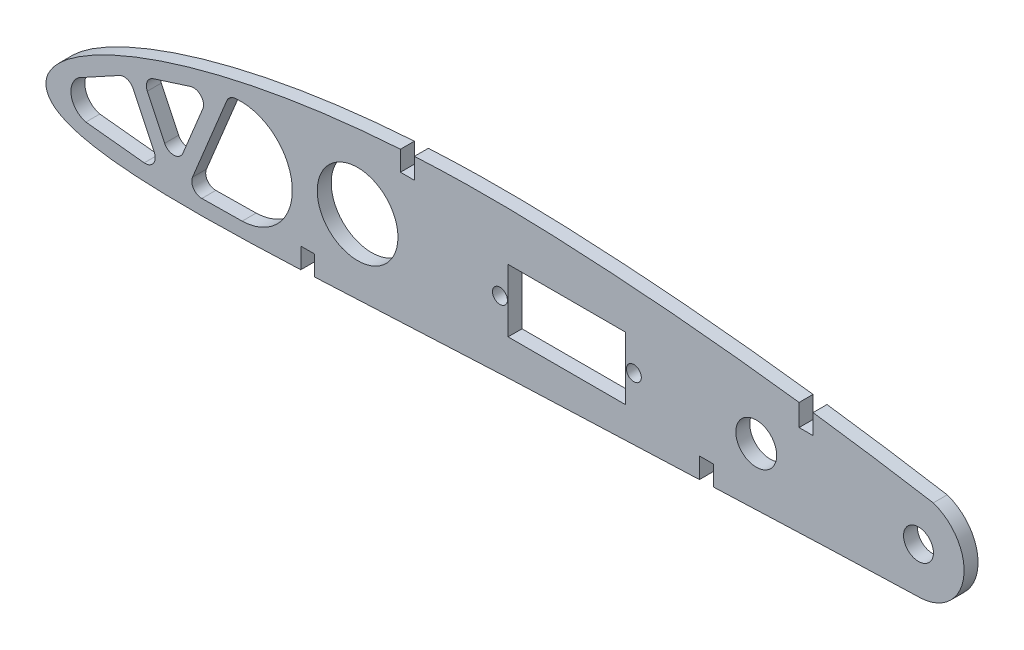
SolidWorks part; units mm, degrees
material "Фанера"
ref_plane "Front" through (0, 0, 0) normal (0, 0, 1) x (1, 0, 0)
ref_plane "Top" through (0, 0, 0) normal (0, 1, 0) x (1, 0, 0)
ref_plane "Right" through (0, 0, 0) normal (1, 0, 0) x (0, 0, -1)
curve "Кривая1"
  spline degree 3 poles (0.048, 0.6214, 0) (0.0227, 0.3735, 0) (-0.0278, -0.1225, 0) (0.078, -0.8844, 0) (0.3497, -1.6388, 0) (0.8143, -2.3651, 0) (1.4635, -3.0393, 0) (2.291, -3.661, 0) (3.3059, -4.2358, 0) (4.5353, -4.7737, 0) (6.0297, -5.2822, 0) (7.869, -5.7653, 0) (10.1688, -6.2217, 0) (13.0754, -6.6396, 0) (16.7281, -6.993, 0) (21.19, -7.2473, 0) (26.4, -7.3766, 0) (32.1974, -7.3763, 0) (38.3978, -7.2614, 0) (44.8576, -7.0566, 0) (51.4865, -6.7865, 0) (58.231, -6.4723, 0) (65.0521, -6.1329, 0) (71.9108, -5.784, 0) (78.7714, -5.4397, 0) (85.6105, -5.111, 0) (92.4321, -4.805, 0) (99.255, -4.532, 0) (106.0974, -4.2783, 0) (112.9692, -4.0031, 0) (119.8644, -3.7232, 0) (126.7739, -3.4401, 0) (133.6816, -3.1587, 0) (140.5819, -2.8824, 0) (147.472, -2.6139, 0) (154.3526, -2.3556, 0) (161.225, -2.1094, 0) (168.0909, -1.8766, 0) (174.9516, -1.6586, 0) (181.8086, -1.4564, 0) (188.6632, -1.2704, 0) (195.5166, -1.1011, 0) (202.3695, -0.9486, 0) (209.2212, -0.8129, 0) (216.0668, -0.6936, 0) (222.8864, -0.5903, 0) (229.6176, -0.5029, 0) (236.0874, -0.4315, 0) (241.9808, -0.3765, 0) (246.559, -0.3395, 0) (249.1205, -0.3213, 0) (250, -0.315, 0) knots 0 0 0 0 0.002941 0.005884 0.009016 0.012365 0.016008 0.020037 0.024574 0.029784 0.035897 0.04324 0.052276 0.063635 0.077983 0.095698 0.11652 0.139661 0.164312 0.189919 0.216157 0.242838 0.269834 0.296993 0.324123 0.351139 0.378036 0.404946 0.431961 0.459078 0.486347 0.513641 0.540929 0.568176 0.59538 0.622543 0.649673 0.676775 0.703855 0.730919 0.757971 0.785018 0.812062 0.839103 0.866132 0.893099 0.919831 0.94581 0.969681 0.98959 1 1 1 1
curve "Кривая2"
  spline degree 3 poles (250, 0.315, 0) (249.1557, 0.545, 0) (246.7202, 1.2085, 0) (242.3913, 2.3583, 0) (236.8498, 3.7876, 0) (230.7799, 5.298, 0) (224.4559, 6.8129, 0) (218.0305, 8.2916, 0) (211.5624, 9.7197, 0) (205.0724, 11.0924, 0) (198.568, 12.4079, 0) (192.0524, 13.6653, 0) (185.5276, 14.8641, 0) (178.9953, 16.0034, 0) (172.4571, 17.0824, 0) (165.9143, 18.0998, 0) (159.3687, 19.0545, 0) (152.8218, 19.9449, 0) (146.2754, 20.7693, 0) (139.7314, 21.5257, 0) (133.1918, 22.212, 0) (126.6587, 22.8257, 0) (120.1368, 23.364, 0) (113.6286, 23.8247, 0) (107.1527, 24.2002, 0) (100.7411, 24.4984, 0) (94.4118, 24.6866, 0) (88.1559, 24.7401, 0) (81.949, 24.6588, 0) (75.7805, 24.441, 0) (69.6537, 24.0819, 0) (63.5754, 23.578, 0) (57.5552, 22.9249, 0) (51.6058, 22.1191, 0) (45.7444, 21.1566, 0) (39.9959, 20.0354, 0) (34.3979, 18.7563, 0) (29.0104, 17.3276, 0) (23.9258, 15.7719, 0) (19.2707, 14.1343, 0) (15.1791, 12.4833, 0) (11.7405, 10.8956, 0) (8.9594, 9.4296, 0) (6.7609, 8.1086, 0) (5.0337, 6.9246, 0) (3.6717, 5.8542, 0) (2.5921, 4.8713, 0) (1.7382, 3.9526, 0) (1.0699, 3.0809, 0) (0.5716, 2.2416, 0) (0.2158, 1.4308, 0) (0.1023, 0.8832, 0) (0.048, 0.6214, 0) knots 0 0 0 0 0.010162 0.029313 0.052012 0.076619 0.101948 0.127526 0.153184 0.178868 0.204558 0.230246 0.255926 0.281594 0.307246 0.332878 0.358485 0.384061 0.409603 0.435104 0.460559 0.485959 0.511303 0.536552 0.561723 0.586629 0.611085 0.635251 0.659272 0.683164 0.706922 0.730536 0.753983 0.777235 0.800246 0.822951 0.845237 0.866916 0.887662 0.906968 0.924203 0.938879 0.950932 0.960693 0.968647 0.975233 0.980795 0.985584 0.989782 0.993521 0.996902 1 1 1 1
sketch "Эскиз2" plane through (0, 0, 0) normal (0, 0, 1) x (1, 0, 0)
  line L0 (-1.2592, 0) -> (250.7702, 0) construction
  line L1 (250.1305, 0) -> (250.1305, 80.0888) construction
  line L2 (0, 0) -> (0, 69.7453) construction
  line L3 (62.5326, 123.1249) -> (62.5326, -48.5934) construction
  line L4 (142.5326, 131.1199) -> (142.5326, -55.0117) construction
  line L5 (62.5326, 8.5923) -> (142.5326, 8.6947) construction
  line L6 (62.5326, 8.5923) -> (150.6431, 8.5923) construction
  line L7 (175.0913, 92.567) -> (175.0913, -39.4544) construction
  line L8 (165.9405, 18.0854) -> (165.9405, -1.9504)
  line L18 (17.4887, 7.868) -> (21.7254, -1.0733)
  line L19 (29.4016, -1.5679) -> (36.2887, 15.1777)
  line L20 (20.3422, 8.8519) -> (23.813, 1.5271)
  line L21 (27.4701, 1.6228) -> (31.461, 11.3265)
  line L22 (7.9994, -2.6904) -> (19.7094, -3.9188)
  line L23 (31.2779, -4.3285) -> (39.3668, -4.221)
  line L24 (6.5801, 4.311) -> (14.7212, 8.7661)
  line L25 (21.5421, 11.6138) -> (29.0038, 13.9928)
  line L26 (72.5326, 27.406) -> (72.5326, 20.4403) construction
  line L27 (52.5326, -12.1202) -> (52.5326, -2.6904) construction
  line L28 (152.5326, 24.4982) -> (152.5326, 15.921) construction
  line L29 (132.5326, -7.5811) -> (132.5326, 3.1811) construction
  line L30 (151.1326, 20.1529) -> (151.1326, 15.7875)
  line L31 (151.1326, 15.7875) -> (153.9326, 15.7875)
  line L32 (153.9326, 15.7875) -> (153.9326, 19.7875)
  line L33 (131.1326, -3.2627) -> (131.1326, 0.8506)
  line L34 (131.1326, 0.8506) -> (133.9326, 0.8506)
  line L35 (133.9326, 0.8506) -> (133.9326, -3.1494)
  line L36 (71.1326, 24.1575) -> (71.1326, 20.1575)
  line L37 (71.1326, 20.1575) -> (73.9326, 20.1575)
  line L38 (73.9326, 20.1575) -> (73.9326, 24.3239)
  line L39 (51.1326, -6.7954) -> (51.1326, -2.6707)
  line L40 (51.1326, -2.6707) -> (53.9326, -2.6707)
  line L41 (53.9326, -2.6707) -> (53.9326, -6.6707)
  line L42 (116.3326, 14.946) -> (119.6026, 14.946) construction
  line L43 (92.7326, 2.346) -> (116.3326, 2.346)
  line L44 (92.7326, 2.346) -> (92.7326, 14.946)
  line L45 (92.7326, 14.946) -> (116.3326, 14.946)
  line L46 (116.3326, 2.346) -> (116.3326, 14.946)
  line L47 (92.7326, 2.346) -> (116.3326, 14.946) construction
  line L48 (92.7326, 14.946) -> (116.3326, 2.346) construction
  line L49 (119.6026, 14.946) -> (119.6026, 2.346) construction
  line L50 (119.6026, 2.346) -> (116.3326, 2.346) construction
  line L51 (104.5326, 11.3265) -> (104.5326, 5.8512) construction
  arc A0 (250, 0.315) -> (250, -0.315) centre (249.685, 0) cw
  circle A3 centre (62.5326, 8.5923) radius 8.1
  circle A5 centre (62.5326, 8.5923) radius 80 construction
  circle A6 centre (142.5326, 8.6947) radius 4.1
  arc A7 (175.0913, 16.6448) -> (175.0913, -1.657) centre (175.0913, 7.4939) ccw
  arc A16 (37.9117, 16.4041) -> (36.2887, 15.1777) centre (38.1384, 14.417) ccw
  arc A20 (6.5801, 4.311) -> (7.9994, -2.6904) centre (8.9558, 1.1481) ccw
  arc A21 (37.9117, 16.4041) -> (39.3668, -4.221) centre (39.0848, 6.123) cw
  arc A22 (23.813, 1.5271) -> (27.4701, 1.6228) centre (25.6204, 2.3835) ccw
  arc A23 (31.461, 11.3265) -> (29.0038, 13.9928) centre (29.6113, 12.0873) ccw
  arc A24 (20.3422, 8.8519) -> (21.5421, 11.6138) centre (22.1496, 9.7083) cw
  arc A25 (17.4887, 7.868) -> (14.7212, 8.7661) centre (15.6813, 7.0116) ccw
  arc A26 (19.7094, -3.9188) -> (21.7254, -1.0733) centre (19.9181, -1.9297) ccw
  arc A27 (29.4016, -1.5679) -> (31.2779, -4.3285) centre (31.2513, -2.3286) ccw
  circle A28 centre (175.0913, 7.4939) radius 3
  circle A29 centre (117.9676, 8.6632) radius 1.5
  circle A30 centre (91.0976, 8.6632) radius 1.5
  circle A31 centre (175.0913, 7.4939) radius 9.1509
  spline S0 degree 3 poles (250, 0.315) (249.1557, 0.545) (246.7202, 1.2085) (242.3913, 2.3583) (236.8498, 3.7876) (230.7799, 5.298) (224.4559, 6.8129) (218.0305, 8.2916) (211.5624, 9.7197) (205.0724, 11.0924) (198.568, 12.4079) (192.0524, 13.6653) (185.5276, 14.8641) (178.9953, 16.0034) (172.4571, 17.0824) (165.9143, 18.0998) (159.3687, 19.0545) (152.8218, 19.9449) (146.2754, 20.7693) (139.7314, 21.5257) (133.1918, 22.212) (126.6587, 22.8257) (120.1368, 23.364) (113.6286, 23.8247) (107.1527, 24.2002) (100.7411, 24.4984) (94.4118, 24.6866) (88.1559, 24.7401) (81.949, 24.6588) (75.7805, 24.441) (69.6537, 24.0819) (63.5754, 23.578) (57.5552, 22.9249) (51.6058, 22.1191) (45.7444, 21.1566) (39.9959, 20.0354) (34.3979, 18.7563) (29.0104, 17.3276) (23.9258, 15.7719) (19.2707, 14.1343) (15.1791, 12.4833) (11.7405, 10.8956) (8.9594, 9.4296) (6.7609, 8.1086) (5.0337, 6.9246) (3.6717, 5.8542) (2.5921, 4.8713) (1.7382, 3.9526) (1.0699, 3.0809) (0.5716, 2.2416) (0.2158, 1.4308) (0.1023, 0.8832) (0.048, 0.6214) knots 0 0 0 0 0.010162 0.029313 0.052012 0.076619 0.101948 0.127526 0.153184 0.178868 0.204558 0.230246 0.255926 0.281594 0.307246 0.332878 0.358485 0.384061 0.409603 0.435104 0.460559 0.485959 0.511303 0.536552 0.561723 0.586629 0.611085 0.635251 0.659272 0.683164 0.706922 0.730536 0.753983 0.777235 0.800246 0.822951 0.845237 0.866916 0.887662 0.906968 0.924203 0.938879 0.950932 0.960693 0.968647 0.975233 0.980795 0.985584 0.989782 0.993521 0.996902 1 1 1 1 construction
  spline S1 degree 3 poles (0.048, 0.6214) (0.0227, 0.3735) (-0.0278, -0.1225) (0.078, -0.8844) (0.3497, -1.6388) (0.8143, -2.3651) (1.4635, -3.0393) (2.291, -3.661) (3.3059, -4.2358) (4.5353, -4.7737) (6.0297, -5.2822) (7.869, -5.7653) (10.1688, -6.2217) (13.0754, -6.6396) (16.7281, -6.993) (21.19, -7.2473) (26.4, -7.3766) (32.1974, -7.3763) (38.3978, -7.2614) (44.8576, -7.0566) (51.4865, -6.7865) (58.231, -6.4723) (65.0521, -6.1329) (71.9108, -5.784) (78.7714, -5.4397) (85.6105, -5.111) (92.4321, -4.805) (99.255, -4.532) (106.0974, -4.2783) (112.9692, -4.0031) (119.8644, -3.7232) (126.7739, -3.4401) (133.6816, -3.1587) (140.5819, -2.8824) (147.472, -2.6139) (154.3526, -2.3556) (161.225, -2.1094) (168.0909, -1.8766) (174.9516, -1.6586) (181.8086, -1.4564) (188.6632, -1.2704) (195.5166, -1.1011) (202.3695, -0.9486) (211.4992, -0.7677) (220.6031, -0.6199) (229.6176, -0.5029) (236.0874, -0.4315) (241.9808, -0.3765) (246.559, -0.3395) (249.1205, -0.3213) (250, -0.315) knots 0 0 0 0 0.002941 0.005884 0.009016 0.012365 0.016008 0.020037 0.024574 0.029784 0.035897 0.04324 0.052276 0.063635 0.077983 0.095698 0.11652 0.139661 0.164312 0.189919 0.216157 0.242838 0.269834 0.296993 0.324123 0.351139 0.378036 0.404946 0.431961 0.459078 0.486347 0.513641 0.540929 0.568176 0.59538 0.622543 0.649673 0.676775 0.703855 0.730919 0.757971 0.785018 0.812062 0.839103 0.893099 0.919831 0.94581 0.969681 0.98959 1 1 1 1 construction
  spline S2 degree 3 poles (250, 0.315) (249.1557, 0.545) (246.7202, 1.2085) (242.3913, 2.3583) (236.8498, 3.7876) (230.7799, 5.298) (224.4559, 6.8129) (218.0305, 8.2916) (211.5624, 9.7197) (205.0724, 11.0924) (198.568, 12.4079) (192.0524, 13.6653) (185.5276, 14.8641) (178.9953, 16.0034) (172.4571, 17.0824) (165.9143, 18.0998) (159.7397, 19.0004) (155.7443, 19.5471) (153.9326, 19.7875) knots 0 0 0 0 0.010162 0.029313 0.052012 0.076619 0.101948 0.127526 0.153184 0.178868 0.204558 0.230246 0.255926 0.281594 0.307246 0.332878 0.358485 0.379707 0.379707 0.379707 0.379707
  spline S3 degree 3 poles (0.048, 0.6214) (0.0227, 0.3735) (-0.0278, -0.1225) (0.078, -0.8844) (0.3497, -1.6388) (0.8143, -2.3651) (1.4635, -3.0393) (2.291, -3.661) (3.3059, -4.2358) (4.5353, -4.7737) (6.0297, -5.2822) (7.869, -5.7653) (10.1688, -6.2217) (13.0754, -6.6396) (16.7281, -6.993) (21.19, -7.2473) (26.4, -7.3766) (32.1974, -7.3763) (38.3978, -7.2614) (44.7521, -7.06) (49.0233, -6.8868) (51.1326, -6.7954) knots 0 0 0 0 0.002941 0.005884 0.009016 0.012365 0.016008 0.020037 0.024574 0.029784 0.035897 0.04324 0.052276 0.063635 0.077983 0.095698 0.11652 0.139661 0.164312 0.189919 0.214908 0.214908 0.214908 0.214908
  spline S4 degree 3 poles (151.1326, 20.1529) (149.5127, 20.3609) (145.7129, 20.8343) (139.7314, 21.5257) (133.1918, 22.212) (126.6587, 22.8257) (120.1368, 23.364) (113.6286, 23.8247) (107.1527, 24.2002) (100.7411, 24.4984) (94.4118, 24.6866) (88.1559, 24.7401) (81.949, 24.6588) (77.2124, 24.4916) (74.545, 24.3569) (73.9326, 24.3239) knots 0.390637 0.390637 0.390637 0.390637 0.409603 0.435104 0.460559 0.485959 0.511303 0.536552 0.561723 0.586629 0.611085 0.635251 0.659272 0.683164 0.690286 0.690286 0.690286 0.690286
  spline S5 degree 3 poles (133.9326, -3.1494) (136.1503, -3.0598) (140.6644, -2.8792) (147.472, -2.6139) (154.3526, -2.3556) (161.225, -2.1094) (168.0909, -1.8766) (174.9516, -1.6586) (181.8086, -1.4564) (188.6632, -1.2704) (195.5166, -1.1011) (202.3695, -0.9486) (211.4992, -0.7677) (220.6031, -0.6199) (229.6176, -0.5029) (236.0874, -0.4315) (241.9808, -0.3765) (246.559, -0.3395) (249.1205, -0.3213) (250, -0.315) knots 0.541906 0.541906 0.541906 0.541906 0.568176 0.59538 0.622543 0.649673 0.676775 0.703855 0.730919 0.757971 0.785018 0.812062 0.839103 0.893099 0.919831 0.94581 0.969681 0.98959 1 1 1 1
  spline S6 degree 3 poles (71.1326, 24.1575) (70.636, 24.1252) (68.1106, 23.954) (63.5754, 23.578) (57.5552, 22.9249) (51.6058, 22.1191) (45.7444, 21.1566) (39.9959, 20.0354) (34.3979, 18.7563) (29.0104, 17.3276) (23.9258, 15.7719) (19.2707, 14.1343) (15.1791, 12.4833) (11.7405, 10.8956) (8.9594, 9.4296) (6.7609, 8.1086) (5.0337, 6.9246) (3.6717, 5.8542) (2.5921, 4.8713) (1.7382, 3.9526) (1.0699, 3.0809) (0.5716, 2.2416) (0.2158, 1.4308) (0.1023, 0.8832) (0.048, 0.6214) knots 0.701143 0.701143 0.701143 0.701143 0.706922 0.730536 0.753983 0.777235 0.800246 0.822951 0.845237 0.866916 0.887662 0.906968 0.924203 0.938879 0.950932 0.960693 0.968647 0.975233 0.980795 0.985584 0.989782 0.993521 0.996902 1 1 1 1
  spline S7 degree 3 poles (53.9326, -6.6707) (55.3566, -6.6057) (59.0587, -6.4311) (65.0521, -6.1329) (71.9108, -5.784) (78.7714, -5.4397) (85.6105, -5.111) (92.4321, -4.805) (99.255, -4.532) (106.0974, -4.2783) (112.9692, -4.0031) (119.8644, -3.7232) (125.9231, -3.4749) (129.6799, -3.3217) (131.1326, -3.2627) knots 0.225966 0.225966 0.225966 0.225966 0.242838 0.269834 0.296993 0.324123 0.351139 0.378036 0.404946 0.431961 0.459078 0.486347 0.513641 0.53085 0.53085 0.53085 0.53085
  point P15 (62.5326, 0)
  point P16 (142.5326, 0)
  point P22 (62.5326, -6.2577)
  point P26 (175.0913, 16.6448)
  point P28 (175.0913, -1.657)
  point P34 (104.5326, 8.646)
  point P48 (117.9676, 14.946)
  point P50 (62.5326, 23.4501)
  point P86 (25.7497, -2.5601)
  point P88 (23.2497, -4.2901)
  point P91 (28.2497, -4.3687)
  dimension "D6" = 16.2
  dimension "D7" = 160
  dimension "D9" = 8.2
  dimension "D12" = 9.1509
  dimension "D29" = 2
  dimension "D14" = 2
  dimension "D30" = 6
  dimension "D17" = 3
  dimension "D2" = 250.1305
  dimension "D4" = 80
  dimension "D11" = 175.0913
  dimension "D13" = 67.8
  dimension "D20" = 5
  dimension "D24" = 5
  dimension "D25" = 3
  dimension "D26" = 3
  dimension "D27" = 5
  dimension "D28" = 2.5
  dimension "D31" = 10
  dimension "D32" = 10
  dimension "D33" = 10
  dimension "D34" = 10
  dimension "D35" = 2.8
  dimension "D36" = 1.4
  dimension "D37" = 4
  dimension "D38" = 2.8
  dimension "D39" = 1.4
  dimension "D40" = 4
  dimension "D42" = 1.4
  dimension "D43" = 4
  dimension "D44" = 1.4
  dimension "D45" = 2.8
  dimension "D46" = 4
  dimension "D15" = 23.6
  dimension "D16" = 12.6
  dimension "D5" = 29.7079
  dimension "D8" = 33.9
  dimension "D10" = 3.27
extrude "Бобышка-Вытянуть2" add sketch "Эскиз2" along normal mid plane 2.8
equation "\"D7@Эскиз2\"=\"D4@Эскиз2\"*2"
equation "\"D11@Эскиз2\"=\"D2@Эскиз2\"*0.7"
equation "\"D28@Эскиз2\"=\"D27@Эскиз2\"/2"
equation "\"D8@Эскиз2\"=\"D13@Эскиз2\"/2"
